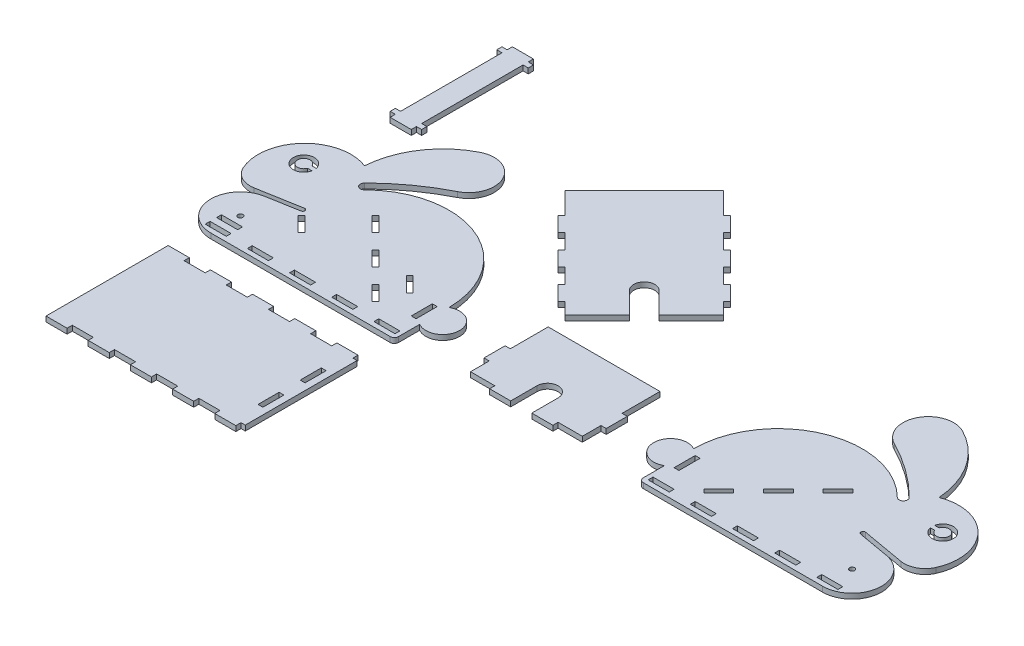
SolidWorks part; units mm, degrees
ref_plane "Front Plane" through (0, 0, 0) normal (0, 0, 1) x (1, 0, 0)
ref_plane "Top Plane" through (0, 0, 0) normal (0, 1, 0) x (1, 0, 0)
ref_plane "Right Plane" through (0, 0, 0) normal (1, 0, 0) x (0, 0, -1)
sketch "Sketch1" plane through (0, 0, 0) normal (0, 1, 0) x (1, 0, 0)
  line L0 (57.15, -63.5) -> (57.15, 63.5) construction
  line L1 (-76.2, 63.5) -> (76.2, 63.5) construction
  line L2 (-76.2, 63.5) -> (-76.2, -63.5) construction
  line L3 (-76.2, -63.5) -> (76.2, -63.5) construction
  line L4 (76.2, 63.5) -> (76.2, -63.5) construction
  line L5 (-76.2, 63.5) -> (76.2, -63.5) construction
  line L6 (-76.2, -63.5) -> (76.2, 63.5) construction
  point P0 (0, 0)
  dimension "D1" = 152.4
  dimension "D2" = 127
  dimension "D3" = 19.05
sketch "Sketch3" plane through (0, 0, 0) normal (0, 1, 0) x (1, 0, 0)
  line L0 (-76.2, -63.5) -> (76.2, -63.5) construction
  line L1 (-76.2, 63.5) -> (-76.2, -63.5) construction
  circle A0 centre (-50.8, -38.1) radius 25.4 construction
  dimension "D1" = 50.8
sketch "Sketch5" plane through (0, 0, 0) normal (0, 1, 0) x (1, 0, 0)
  line L1 (6.35, -55.88) -> (57.15, -55.88) construction
  line L2 (31.75, -55.88) -> (31.75, -63.5) construction
  line L3 (-76.2, -63.5) -> (76.2, -63.5) construction
  line L4 (57.15, -63.5) -> (57.15, 63.5) construction
  arc A0 (6.35, -55.88) -> (57.15, -55.88) centre (31.75, -17.3567) ccw construction
  dimension "D1" = 7.62
  dimension "D2" = 50.8
sketch "Sketch6" plane through (0, 0, 0) normal (0, 1, 0) x (1, 0, 0)
  line L0 (-50.8, -38.1) -> (-50.8, -55.88) construction
  line L1 (-50.8, -55.88) -> (57.15, -55.88) construction
  line L2 (-53.8875, -20.5901) -> (-35.1269, -17.2821) construction
  line L3 (-35.5679, -14.7807) -> (-35.1269, -17.2821) construction
  line L4 (-53.8875, -20.5901) -> (-35.1269, -20.5901) construction
  line L5 (-35.1269, -20.5901) -> (-35.1269, -17.2821) construction
  line L6 (-35.5679, -14.7807) -> (-61.3497, -19.3267) construction
  line L7 (59.69, -53.34) -> (57.15, -53.34) construction
  line L8 (57.15, -53.34) -> (57.15, -55.88) construction
  line L9 (59.69, -53.34) -> (59.69, -40.64) construction
  line L10 (59.69, -40.64) -> (64.77, -31.8412) construction
  line L11 (64.77, -31.8412) -> (59.69, -23.0424) construction
  line L12 (59.69, -23.0424) -> (59.69, -40.64) construction
  line L13 (-27.031, 12.8787) -> (8.89, -23.0424) construction
  line L14 (8.89, -23.0424) -> (59.69, -23.0424) construction
  line L15 (-27.031, 12.8787) -> (-28.8271, 14.6747) construction
  line L16 (-28.8271, 14.6747) -> (-30.6231, 16.4708) construction
  line L17 (-30.6231, 16.4708) -> (-39.6034, 25.451) construction
  line L18 (-11.8373, 67.2263) -> (-4.9647, 53.6239) construction
  line L19 (-4.9647, 53.6239) -> (1.9078, 40.0215) construction
  line L20 (-75.1597, -11.9793) -> (-49.6295, -0.6281) construction
  line L21 (-49.6295, -0.6281) -> (-39.6034, 25.451) construction
  line L22 (-59.0189, 8.2912) -> (-75.1597, -11.9793) construction
  line L23 (-59.0189, 8.2912) -> (-39.6034, 25.451) construction
  line L26 (-55.4268, 9.5612) -> (-52.7972, 9.5612) construction
  line L27 (-55.4268, 7.0212) -> (-52.7972, 7.0212) construction
  line L28 (-52.7972, 9.5612) -> (-52.7972, 7.0212) construction
  line L29 (-55.4268, 9.5612) -> (-55.4268, 7.0212) construction
  arc A0 (-50.8, -55.88) -> (-53.8875, -20.5901) centre (-50.8, -38.1) cw construction
  arc A1 (-35.1269, -17.2821) -> (-35.5679, -14.7807) centre (-35.3474, -16.0314) ccw construction
  arc A2 (57.15, -55.88) -> (59.69, -53.34) centre (57.15, -53.34) ccw construction
  arc A3 (59.69, -40.64) -> (59.69, -23.0424) centre (64.77, -31.8412) ccw construction
  arc A4 (59.69, -23.0424) -> (-27.031, 12.8787) centre (8.89, -23.0424) ccw construction
  arc A5 (-27.031, 12.8787) -> (-30.6231, 16.4708) centre (-28.8271, 14.6747) cw construction
  arc A6 (-30.6231, 16.4708) -> (1.9078, 40.0215) centre (59.1794, -73.3318) cw construction
  arc A7 (1.9078, 40.0215) -> (-11.8373, 67.2263) centre (-4.9647, 53.6239) ccw construction
  arc A8 (-11.8373, 67.2263) -> (-39.6034, 25.451) centre (11.0713, 21.885) ccw construction
  arc A9 (-61.3497, -19.3267) -> (-75.1597, -11.9793) centre (-63.5551, -6.8197) cw construction
  arc A10 (-75.1597, -11.9793) -> (-39.6034, 25.451) centre (-49.6295, -0.6281) cw construction
  arc A11 (-55.4268, 9.5612) -> (-55.4268, 7.0212) centre (-59.0189, 8.2912) ccw construction
  arc A13 (-52.7972, 9.5612) -> (-52.7972, 7.0212) centre (-59.0189, 8.2912) ccw construction
  dimension "D2" = 1.27
  dimension "D3" = 2.54
  dimension "D5" = 10.16
  dimension "D8" = 2.54
  dimension "D11" = 15.24
  dimension "D12" = 127
  dimension "D13" = 50.8
  dimension "D15" = 12.7
  dimension "D16" = 27.94
  dimension "D18" = 7.62
  dimension "D19" = 2.54
  dimension "D1" = 10
  dimension "D4" = 30
  dimension "D6" = 12.7
  dimension "D7" = 135
  dimension "D9" = 180
  dimension "D10" = 50.8
  dimension "D14" = 12.7
  dimension "D17" = 135
  dimension "D20" = 170
  dimension "D21" = 2.54
  dimension "D22" = 19.05
sketch "Sketch7" plane through (0, 0, 0) normal (0, 1, 0) x (1, 0, 0)
  line L0 (-50.8, -55.88) -> (57.15, -55.88) construction
  line L1 (59.69, -53.34) -> (59.69, -40.64) construction
  line L2 (-35.5679, -14.7807) -> (-61.3497, -19.3267) construction
  line L3 (-53.8875, -20.5901) -> (-35.1269, -17.2821) construction
  line L4 (25.4, -51.4985) -> (0, -51.4985) construction
  line L5 (19.05, -50.038) -> (31.75, -50.038)
  line L6 (-50.8, -55.88) -> (57.15, -55.88)
  line L7 (59.69, -53.34) -> (59.69, -40.64)
  line L8 (-35.5679, -14.7807) -> (-61.3497, -19.3267)
  line L9 (-53.8875, -20.5901) -> (-35.1269, -17.2821)
  line L10 (-55.4268, 9.5612) -> (-52.7972, 9.5612) construction
  line L11 (-55.4268, 7.0212) -> (-52.7972, 7.0212) construction
  line L12 (-55.4268, 9.5612) -> (-52.7972, 9.5612)
  line L13 (-55.4268, 7.0212) -> (-52.7972, 7.0212)
  line L14 (50.8, -51.4985) -> (25.4, -51.4985) construction
  line L15 (44.45, -50.038) -> (57.15, -50.038)
  line L16 (44.45, -50.038) -> (44.45, -52.959)
  line L17 (44.45, -52.959) -> (57.15, -52.959)
  line L18 (57.15, -50.038) -> (57.15, -52.959)
  line L19 (44.45, -50.038) -> (57.15, -52.959) construction
  line L20 (44.45, -52.959) -> (57.15, -50.038) construction
  line L21 (19.05, -50.038) -> (19.05, -52.959)
  line L22 (19.05, -52.959) -> (31.75, -52.959)
  line L23 (31.75, -50.038) -> (31.75, -52.959)
  line L24 (19.05, -50.038) -> (31.75, -52.959) construction
  line L25 (19.05, -52.959) -> (31.75, -50.038) construction
  line L26 (0, -51.4985) -> (-25.4, -51.4985) construction
  line L27 (-6.35, -50.038) -> (6.35, -50.038)
  line L28 (-6.35, -50.038) -> (-6.35, -52.959)
  line L29 (-6.35, -52.959) -> (6.35, -52.959)
  line L30 (6.35, -50.038) -> (6.35, -52.959)
  line L31 (-6.35, -50.038) -> (6.35, -52.959) construction
  line L32 (-6.35, -52.959) -> (6.35, -50.038) construction
  line L33 (-25.4, -51.4985) -> (-50.8, -51.4985) construction
  line L34 (-31.75, -50.038) -> (-19.05, -50.038)
  line L35 (-31.75, -50.038) -> (-31.75, -52.959)
  line L36 (-31.75, -52.959) -> (-19.05, -52.959)
  line L37 (-19.05, -50.038) -> (-19.05, -52.959)
  line L38 (-31.75, -50.038) -> (-19.05, -52.959) construction
  line L39 (-31.75, -52.959) -> (-19.05, -50.038) construction
  line L40 (57.15, -51.4985) -> (54.229, -51.4985) construction
  line L41 (-57.15, -50.038) -> (-44.45, -50.038)
  line L42 (-57.15, -50.038) -> (-57.15, -52.959)
  line L43 (-57.15, -52.959) -> (-44.45, -52.959)
  line L44 (-44.45, -50.038) -> (-44.45, -52.959)
  line L45 (-57.15, -50.038) -> (-44.45, -52.959) construction
  line L46 (-57.15, -52.959) -> (-44.45, -50.038) construction
  line L47 (54.229, -51.4985) -> (54.229, -32.4485) construction
  line L49 (52.7685, -26.0985) -> (55.6895, -26.0985)
  line L50 (52.7685, -26.0985) -> (52.7685, -38.7985)
  line L51 (52.7685, -38.7985) -> (55.6895, -38.7985)
  line L52 (55.6895, -26.0985) -> (55.6895, -38.7985)
  line L53 (52.7685, -26.0985) -> (55.6895, -38.7985) construction
  line L54 (52.7685, -38.7985) -> (55.6895, -26.0985) construction
  arc A0 (-53.8875, -20.5901) -> (-50.8, -55.88) centre (-50.8, -38.1) ccw construction
  arc A1 (57.15, -55.88) -> (59.69, -53.34) centre (57.15, -53.34) ccw construction
  arc A2 (59.69, -40.64) -> (59.69, -23.0424) centre (64.77, -31.8412) ccw construction
  arc A3 (59.69, -23.0424) -> (-27.031, 12.8787) centre (8.89, -23.0424) ccw construction
  arc A4 (-30.6231, 16.4708) -> (-27.031, 12.8787) centre (-28.8271, 14.6747) ccw construction
  arc A5 (1.9078, 40.0215) -> (-30.6231, 16.4708) centre (59.1794, -73.3318) ccw construction
  arc A6 (1.9078, 40.0215) -> (-11.8373, 67.2263) centre (-4.9647, 53.6239) ccw construction
  arc A7 (-11.8373, 67.2263) -> (-39.6034, 25.451) centre (11.0713, 21.885) ccw construction
  arc A8 (-39.6034, 25.451) -> (-75.1597, -11.9793) centre (-49.6295, -0.6281) ccw construction
  arc A9 (-75.1597, -11.9793) -> (-61.3497, -19.3267) centre (-63.5551, -6.8197) ccw construction
  arc A10 (-35.1269, -17.2821) -> (-35.5679, -14.7807) centre (-35.3474, -16.0314) ccw construction
  arc A13 (-53.8875, -20.5901) -> (-50.8, -55.88) centre (-50.8, -38.1) ccw
  arc A14 (57.15, -55.88) -> (59.69, -53.34) centre (57.15, -53.34) ccw
  arc A15 (59.69, -40.64) -> (59.69, -23.0424) centre (64.77, -31.8412) ccw
  arc A16 (59.69, -23.0424) -> (-27.031, 12.8787) centre (8.89, -23.0424) ccw
  arc A17 (-30.6231, 16.4708) -> (-27.031, 12.8787) centre (-28.8271, 14.6747) ccw
  arc A18 (1.9078, 40.0215) -> (-30.6231, 16.4708) centre (59.1794, -73.3318) ccw
  arc A19 (1.9078, 40.0215) -> (-11.8373, 67.2263) centre (-4.9647, 53.6239) ccw
  arc A20 (-11.8373, 67.2263) -> (-39.6034, 25.451) centre (11.0713, 21.885) ccw
  arc A21 (-39.6034, 25.451) -> (-75.1597, -11.9793) centre (-49.6295, -0.6281) ccw
  arc A22 (-75.1597, -11.9793) -> (-61.3497, -19.3267) centre (-63.5551, -6.8197) ccw
  arc A23 (-35.1269, -17.2821) -> (-35.5679, -14.7807) centre (-35.3474, -16.0314) ccw
  arc A24 (-55.4268, 9.5612) -> (-55.4268, 7.0212) centre (-59.0189, 8.2912) ccw construction
  arc A25 (-52.7972, 9.5612) -> (-52.7972, 7.0212) centre (-59.0189, 8.2912) ccw construction
  arc A26 (-55.4268, 9.5612) -> (-55.4268, 7.0212) centre (-59.0189, 8.2912) ccw
  arc A27 (-52.7972, 9.5612) -> (-52.7972, 7.0212) centre (-59.0189, 8.2912) ccw
  point P29 (50.8, -51.4985)
  dimension "D1" = 2.921
  dimension "D2" = 12.7
  dimension "D3" = 2.921
  dimension "D4" = 2.54
  dimension "D5" = 25.4
  dimension "D6" = 19.05
sketch "Sketch9" plane through (0, 0, 0) normal (0, 1, 0) x (1, 0, 0)
  line L0 (-39.0097, 50.0021) -> (52.7685, -41.7762) construction
  line L1 (-39.0097, 50.0021) -> (-47.2716, 41.7402) construction
  line L2 (52.7685, -41.7762) -> (44.5067, -50.038) construction
  line L3 (-47.2716, 41.7402) -> (44.5067, -50.038) construction
  line L4 (-39.0097, 50.0021) -> (44.5067, -50.038) construction
  line L5 (52.7685, -41.7762) -> (-47.2716, 41.7402) construction
  line L6 (2.7485, -0.018) -> (2.7485, -55.88) construction
  line L7 (-50.8, -55.88) -> (57.15, -55.88) construction
  line L8 (44.5067, -50.038) -> (7.2565, -50.038) construction
  line L9 (19.05, -50.038) -> (31.75, -50.038) construction
  line L11 (52.7685, -26.0985) -> (52.7685, -38.7985) construction
  point P1 (2.7485, -0.018)
  dimension "D1" = 129.794
  dimension "D2" = 11.684
  dimension "D3" = 45
sketch "Sketch10" plane through (0, 0, 0) normal (0, 1, 0) x (1, 0, 0)
  line L0 (24.4807, -34.1429) -> (33.4609, -43.1232)
  line L1 (24.4807, -34.1429) -> (26.5462, -32.0775)
  line L2 (33.4609, -43.1232) -> (35.5264, -41.0577)
  line L3 (26.5462, -32.0775) -> (35.5264, -41.0577)
  line L4 (24.4807, -34.1429) -> (35.5264, -41.0577) construction
  line L5 (33.4609, -43.1232) -> (26.5462, -32.0775) construction
  line L6 (44.45, -50.038) -> (57.15, -50.038) construction
  line L7 (57.15, -50.038) -> (57.15, -52.959) construction
  line L8 (-47.2716, 41.7402) -> (44.5067, -50.038) construction
  line L9 (30.0036, -37.6003) -> (12.043, -19.6398) construction
  line L10 (25.4, -51.4985) -> (0, -51.4985) construction
  line L11 (8.5856, -14.117) -> (17.5659, -23.0972)
  line L12 (8.5856, -14.117) -> (6.5202, -16.1824)
  line L13 (17.5659, -23.0972) -> (15.5004, -25.1627)
  line L14 (6.5202, -16.1824) -> (15.5004, -25.1627)
  line L15 (8.5856, -14.117) -> (15.5004, -25.1627) construction
  line L16 (17.5659, -23.0972) -> (6.5202, -16.1824) construction
  line L18 (12.043, -19.6398) -> (-5.9175, -1.6793) construction
  line L19 (-9.3749, 3.8435) -> (-0.3946, -5.1367)
  line L20 (-9.3749, 3.8435) -> (-11.4403, 1.7781)
  line L21 (-0.3946, -5.1367) -> (-2.4601, -7.2022)
  line L22 (-11.4403, 1.7781) -> (-2.4601, -7.2022)
  line L23 (-9.3749, 3.8435) -> (-2.4601, -7.2022) construction
  line L24 (-0.3946, -5.1367) -> (-11.4403, 1.7781) construction
  point P1 (30.0036, -37.6003)
  dimension "D1" = 12.7
sketch "Sketch11" plane through (0, 0, 0) normal (0, 1, 0) x (1, 0, 0)
  line L0 (-31.75, -50.038) -> (-19.05, -50.038) construction
  line L1 (-35.8243, -24.638) -> (14.9757, -24.638) construction
  line L2 (-35.8243, -24.638) -> (-35.8243, -50.038) construction
  line L3 (-35.8243, -50.038) -> (14.9757, -50.038) construction
  line L4 (14.9757, -24.638) -> (14.9757, -50.038) construction
  line L5 (-35.8243, -24.638) -> (14.9757, -50.038) construction
  line L6 (-35.8243, -50.038) -> (14.9757, -24.638) construction
  line L7 (6.5202, -16.1824) -> (15.5004, -25.1627) construction
  point P0 (-10.4243, -37.338)
  dimension "D1" = 25.4
  dimension "D2" = 50.8
sketch "Sketch12" plane through (0, 0, 0) normal (0, 1, 0) x (1, 0, 0)
  line L0 (59.69, -53.34) -> (59.69, -40.64) construction
  line L1 (55.6895, -26.0985) -> (55.6895, -38.7985) construction
  line L2 (52.7685, -26.0985) -> (55.6895, -26.0985) construction
  line L3 (52.7685, -26.0985) -> (52.7685, -38.7985) construction
  line L4 (52.7685, -38.7985) -> (55.6895, -38.7985) construction
  line L5 (-50.8, -55.88) -> (57.15, -55.88) construction
  line L6 (44.45, -52.959) -> (57.15, -52.959) construction
  line L7 (57.15, -50.038) -> (57.15, -52.959) construction
  line L8 (44.45, -50.038) -> (57.15, -50.038) construction
  line L9 (44.45, -50.038) -> (44.45, -52.959) construction
  line L10 (19.05, -50.038) -> (31.75, -50.038) construction
  line L11 (19.05, -52.959) -> (31.75, -52.959) construction
  line L12 (31.75, -50.038) -> (31.75, -52.959) construction
  line L13 (19.05, -50.038) -> (19.05, -52.959) construction
  line L14 (6.35, -50.038) -> (6.35, -52.959) construction
  line L15 (-6.35, -50.038) -> (6.35, -50.038) construction
  line L16 (-6.35, -52.959) -> (6.35, -52.959) construction
  line L17 (-6.35, -50.038) -> (-6.35, -52.959) construction
  line L18 (-19.05, -50.038) -> (-19.05, -52.959) construction
  line L19 (-31.75, -50.038) -> (-19.05, -50.038) construction
  line L20 (-31.75, -52.959) -> (-19.05, -52.959) construction
  line L21 (-31.75, -50.038) -> (-31.75, -52.959) construction
  line L22 (-57.15, -50.038) -> (-44.45, -50.038) construction
  line L23 (-44.45, -50.038) -> (-44.45, -52.959) construction
  line L24 (-57.15, -52.959) -> (-44.45, -52.959) construction
  line L25 (-57.15, -50.038) -> (-57.15, -52.959) construction
  line L26 (-53.8875, -20.5901) -> (-35.1269, -17.2821) construction
  line L27 (-35.5679, -14.7807) -> (-61.3497, -19.3267) construction
  line L28 (-9.3749, 3.8435) -> (-11.4403, 1.7781) construction
  line L29 (-11.4403, 1.7781) -> (-2.4601, -7.2022) construction
  line L30 (-0.3946, -5.1367) -> (-2.4601, -7.2022) construction
  line L31 (-9.3749, 3.8435) -> (-0.3946, -5.1367) construction
  line L32 (6.5202, -16.1824) -> (15.5004, -25.1627) construction
  line L33 (8.5856, -14.117) -> (6.5202, -16.1824) construction
  line L34 (17.5659, -23.0972) -> (15.5004, -25.1627) construction
  line L35 (59.69, -53.34) -> (59.69, -40.64)
  line L36 (55.6895, -26.0985) -> (55.6895, -38.7985)
  line L37 (52.7685, -26.0985) -> (55.6895, -26.0985)
  line L38 (52.7685, -26.0985) -> (52.7685, -38.7985)
  line L39 (52.7685, -38.7985) -> (55.6895, -38.7985)
  line L40 (-50.8, -55.88) -> (57.15, -55.88)
  line L41 (44.45, -52.959) -> (57.15, -52.959)
  line L42 (57.15, -50.038) -> (57.15, -52.959)
  line L43 (44.45, -50.038) -> (57.15, -50.038)
  line L44 (44.45, -50.038) -> (44.45, -52.959)
  line L45 (19.05, -50.038) -> (31.75, -50.038)
  line L46 (19.05, -52.959) -> (31.75, -52.959)
  line L47 (31.75, -50.038) -> (31.75, -52.959)
  line L48 (19.05, -50.038) -> (19.05, -52.959)
  line L49 (6.35, -50.038) -> (6.35, -52.959)
  line L50 (-6.35, -50.038) -> (6.35, -50.038)
  line L51 (-6.35, -52.959) -> (6.35, -52.959)
  line L52 (-6.35, -50.038) -> (-6.35, -52.959)
  line L53 (-19.05, -50.038) -> (-19.05, -52.959)
  line L54 (-31.75, -50.038) -> (-19.05, -50.038)
  line L55 (-31.75, -52.959) -> (-19.05, -52.959)
  line L56 (-31.75, -50.038) -> (-31.75, -52.959)
  line L57 (-57.15, -50.038) -> (-44.45, -50.038)
  line L58 (-44.45, -50.038) -> (-44.45, -52.959)
  line L59 (-57.15, -52.959) -> (-44.45, -52.959)
  line L60 (-57.15, -50.038) -> (-57.15, -52.959)
  line L61 (-53.8875, -20.5901) -> (-35.1269, -17.2821)
  line L62 (-35.5679, -14.7807) -> (-61.3497, -19.3267)
  line L63 (-9.3749, 3.8435) -> (-11.4403, 1.7781)
  line L64 (-11.4403, 1.7781) -> (-2.4601, -7.2022)
  line L65 (-0.3946, -5.1367) -> (-2.4601, -7.2022)
  line L66 (-9.3749, 3.8435) -> (-0.3946, -5.1367)
  line L67 (6.5202, -16.1824) -> (15.5004, -25.1627)
  line L68 (8.5856, -14.117) -> (6.5202, -16.1824)
  line L69 (17.5659, -23.0972) -> (15.5004, -25.1627)
  line L70 (8.5856, -14.117) -> (17.5659, -23.0972) construction
  line L71 (26.5462, -32.0775) -> (35.5264, -41.0577) construction
  line L72 (24.4807, -34.1429) -> (26.5462, -32.0775) construction
  line L73 (24.4807, -34.1429) -> (33.4609, -43.1232) construction
  line L74 (33.4609, -43.1232) -> (35.5264, -41.0577) construction
  line L75 (8.5856, -14.117) -> (17.5659, -23.0972)
  line L76 (26.5462, -32.0775) -> (35.5264, -41.0577)
  line L77 (24.4807, -34.1429) -> (26.5462, -32.0775)
  line L78 (24.4807, -34.1429) -> (33.4609, -43.1232)
  line L79 (33.4609, -43.1232) -> (35.5264, -41.0577)
  line L80 (-55.4268, 9.5612) -> (-52.7972, 9.5612) construction
  line L81 (-55.4268, 7.0212) -> (-52.7972, 7.0212) construction
  line L82 (-55.4268, 9.5612) -> (-52.7972, 9.5612)
  line L83 (-55.4268, 7.0212) -> (-52.7972, 7.0212)
  line L84 (57.15, -51.4985) -> (133.35, -51.4985) construction
  line L85 (133.35, -51.4985) -> (133.35, -26.0985) construction
  line L86 (322.1268, 7.0212) -> (319.4972, 7.0212)
  line L87 (322.1268, 9.5612) -> (319.4972, 9.5612)
  line L88 (233.2391, -43.1232) -> (231.1736, -41.0577)
  line L89 (242.2193, -34.1429) -> (233.2391, -43.1232)
  line L90 (242.2193, -34.1429) -> (240.1538, -32.0775)
  line L91 (240.1538, -32.0775) -> (231.1736, -41.0577)
  line L92 (258.1144, -14.117) -> (249.1341, -23.0972)
  line L93 (249.1341, -23.0972) -> (251.1996, -25.1627)
  line L94 (258.1144, -14.117) -> (260.1798, -16.1824)
  line L95 (260.1798, -16.1824) -> (251.1996, -25.1627)
  line L96 (276.0749, 3.8435) -> (267.0946, -5.1367)
  line L97 (267.0946, -5.1367) -> (269.1601, -7.2022)
  line L98 (278.1403, 1.7781) -> (269.1601, -7.2022)
  line L99 (276.0749, 3.8435) -> (278.1403, 1.7781)
  line L100 (302.2679, -14.7807) -> (328.0497, -19.3267)
  line L101 (320.5875, -20.5901) -> (301.8269, -17.2821)
  line L102 (323.85, -50.038) -> (323.85, -52.959)
  line L103 (323.85, -52.959) -> (311.15, -52.959)
  line L104 (311.15, -50.038) -> (311.15, -52.959)
  line L105 (323.85, -50.038) -> (311.15, -50.038)
  line L106 (298.45, -50.038) -> (298.45, -52.959)
  line L107 (298.45, -52.959) -> (285.75, -52.959)
  line L108 (298.45, -50.038) -> (285.75, -50.038)
  line L109 (285.75, -50.038) -> (285.75, -52.959)
  line L110 (273.05, -50.038) -> (273.05, -52.959)
  line L111 (273.05, -52.959) -> (260.35, -52.959)
  line L112 (273.05, -50.038) -> (260.35, -50.038)
  line L113 (260.35, -50.038) -> (260.35, -52.959)
  line L114 (247.65, -50.038) -> (247.65, -52.959)
  line L115 (234.95, -50.038) -> (234.95, -52.959)
  line L116 (247.65, -52.959) -> (234.95, -52.959)
  line L117 (247.65, -50.038) -> (234.95, -50.038)
  line L118 (222.25, -50.038) -> (222.25, -52.959)
  line L119 (222.25, -50.038) -> (209.55, -50.038)
  line L120 (209.55, -50.038) -> (209.55, -52.959)
  line L121 (222.25, -52.959) -> (209.55, -52.959)
  line L122 (317.5, -55.88) -> (209.55, -55.88)
  line L123 (213.9315, -38.7985) -> (211.0105, -38.7985)
  line L124 (213.9315, -26.0985) -> (213.9315, -38.7985)
  line L125 (213.9315, -26.0985) -> (211.0105, -26.0985)
  line L126 (211.0105, -26.0985) -> (211.0105, -38.7985)
  line L127 (207.01, -53.34) -> (207.01, -40.64)
  line L128 (-50.8, -38.1) -> (-50.8, -44.6405) construction
  line L129 (-57.15, -43.18) -> (-44.45, -43.18)
  line L130 (-57.15, -43.18) -> (-57.15, -46.101)
  line L131 (-57.15, -46.101) -> (-44.45, -46.101)
  line L132 (-44.45, -43.18) -> (-44.45, -46.101)
  line L133 (-57.15, -43.18) -> (-44.45, -46.101) construction
  line L134 (-57.15, -46.101) -> (-44.45, -43.18) construction
  line L135 (-44.9915, -5.0819) -> (-9.0705, -41.0029) construction
  line L136 (-56.9702, 67.9626) -> (34.808, -23.8157) construction
  line L137 (-44.9915, -5.0819) -> (-24.786, 15.1237) construction
  line L138 (-39.0097, 50.0021) -> (52.7685, -41.7762) construction
  line L139 (-65.2321, 59.7007) -> (26.5462, -32.0775) construction
  line L140 (-47.2716, 41.7402) -> (44.5067, -50.038) construction
  line L141 (26.5462, -32.0775) -> (34.808, -23.8157) construction
  line L142 (-65.2321, 59.7007) -> (-56.9702, 67.9626) construction
  line L143 (30.3179, -19.3255) -> (39.2981, -28.3058)
  line L144 (30.3179, -19.3255) -> (32.3833, -17.2601)
  line L145 (39.2981, -28.3058) -> (41.3636, -26.2403)
  line L146 (32.3833, -17.2601) -> (41.3636, -26.2403)
  line L147 (30.3179, -19.3255) -> (41.3636, -26.2403) construction
  line L148 (39.2981, -28.3058) -> (32.3833, -17.2601) construction
  line L149 (-9.0705, -41.0029) -> (11.1351, -20.7973) construction
  line L150 (-24.786, 15.1237) -> (11.1351, -20.7973) construction
  line L151 (-44.9915, -5.0819) -> (11.1351, -20.7973) construction
  line L152 (-9.0705, -41.0029) -> (-24.786, 15.1237) construction
  line L153 (-33.7114, -20.493) -> (-24.7311, -29.4732)
  line L154 (-33.7114, -20.493) -> (-31.6459, -18.4275)
  line L155 (-24.7311, -29.4732) -> (-22.6657, -27.4078)
  line L156 (-31.6459, -18.4275) -> (-22.6657, -27.4078)
  line L157 (-33.7114, -20.493) -> (-22.6657, -27.4078) construction
  line L158 (-24.7311, -29.4732) -> (-31.6459, -18.4275) construction
  line L159 (-33.7114, -20.493) -> (-35.7768, -18.4275) construction
  line L160 (-35.7768, -18.4275) -> (-33.7114, -16.362) construction
  line L161 (-33.7114, -16.362) -> (-31.6459, -18.4275) construction
  line L162 (-31.6459, -18.4275) -> (-33.7114, -16.362) construction
  arc A0 (-39.6034, 25.451) -> (-75.1597, -11.9793) centre (-49.6295, -0.6281) ccw construction
  arc A1 (-11.8373, 67.2263) -> (-39.6034, 25.451) centre (11.0713, 21.885) ccw construction
  arc A2 (1.9078, 40.0215) -> (-11.8373, 67.2263) centre (-4.9647, 53.6239) ccw construction
  arc A3 (1.9078, 40.0215) -> (-30.6231, 16.4708) centre (59.1794, -73.3318) ccw construction
  arc A4 (-30.6231, 16.4708) -> (-27.031, 12.8787) centre (-28.8271, 14.6747) ccw construction
  arc A5 (59.69, -23.0424) -> (-27.031, 12.8787) centre (8.89, -23.0424) ccw construction
  arc A6 (59.69, -40.64) -> (59.69, -23.0424) centre (64.77, -31.8412) ccw construction
  arc A7 (57.15, -55.88) -> (59.69, -53.34) centre (57.15, -53.34) ccw construction
  arc A8 (-53.8875, -20.5901) -> (-50.8, -55.88) centre (-50.8, -38.1) ccw construction
  arc A9 (-35.1269, -17.2821) -> (-35.5679, -14.7807) centre (-35.3474, -16.0314) ccw construction
  arc A10 (-75.1597, -11.9793) -> (-61.3497, -19.3267) centre (-63.5551, -6.8197) ccw construction
  arc A11 (-39.6034, 25.451) -> (-75.1597, -11.9793) centre (-49.6295, -0.6281) ccw
  arc A12 (-11.8373, 67.2263) -> (-39.6034, 25.451) centre (11.0713, 21.885) ccw
  arc A13 (1.9078, 40.0215) -> (-11.8373, 67.2263) centre (-4.9647, 53.6239) ccw
  arc A14 (1.9078, 40.0215) -> (-30.6231, 16.4708) centre (59.1794, -73.3318) ccw
  arc A15 (-30.6231, 16.4708) -> (-27.031, 12.8787) centre (-28.8271, 14.6747) ccw
  arc A16 (59.69, -23.0424) -> (-27.031, 12.8787) centre (8.89, -23.0424) ccw
  arc A17 (59.69, -40.64) -> (59.69, -23.0424) centre (64.77, -31.8412) ccw
  arc A18 (57.15, -55.88) -> (59.69, -53.34) centre (57.15, -53.34) ccw
  arc A19 (-53.8875, -20.5901) -> (-50.8, -55.88) centre (-50.8, -38.1) ccw
  arc A20 (-35.1269, -17.2821) -> (-35.5679, -14.7807) centre (-35.3474, -16.0314) ccw
  arc A21 (-75.1597, -11.9793) -> (-61.3497, -19.3267) centre (-63.5551, -6.8197) ccw
  arc A22 (-52.7972, 9.5612) -> (-52.7972, 7.0212) centre (-59.0189, 8.2912) ccw construction
  arc A23 (-55.4268, 9.5612) -> (-55.4268, 7.0212) centre (-59.0189, 8.2912) ccw construction
  arc A24 (-52.7972, 9.5612) -> (-52.7972, 7.0212) centre (-59.0189, 8.2912) ccw
  arc A25 (-55.4268, 9.5612) -> (-55.4268, 7.0212) centre (-59.0189, 8.2912) ccw
  circle A26 centre (-50.8, -38.1) radius 1.524
  circle A27 centre (317.5, -38.1) radius 1.524
  arc A28 (322.1268, 9.5612) -> (322.1268, 7.0212) centre (325.7189, 8.2912) cw
  arc A29 (319.4972, 9.5612) -> (319.4972, 7.0212) centre (325.7189, 8.2912) cw
  arc A30 (341.8597, -11.9793) -> (328.0497, -19.3267) centre (330.2551, -6.8197) cw
  arc A31 (301.8269, -17.2821) -> (302.2679, -14.7807) centre (302.0474, -16.0314) cw
  arc A32 (320.5875, -20.5901) -> (317.5, -55.88) centre (317.5, -38.1) cw
  arc A33 (209.55, -55.88) -> (207.01, -53.34) centre (209.55, -53.34) cw
  arc A34 (207.01, -40.64) -> (207.01, -23.0424) centre (201.93, -31.8412) cw
  arc A35 (207.01, -23.0424) -> (293.731, 12.8787) centre (257.81, -23.0424) cw
  arc A36 (297.3231, 16.4708) -> (293.731, 12.8787) centre (295.5271, 14.6747) cw
  arc A37 (264.7922, 40.0215) -> (297.3231, 16.4708) centre (207.5206, -73.3318) cw
  arc A38 (264.7922, 40.0215) -> (278.5373, 67.2263) centre (271.6647, 53.6239) cw
  arc A39 (278.5373, 67.2263) -> (306.3034, 25.451) centre (255.6287, 21.885) cw
  arc A40 (306.3034, 25.451) -> (341.8597, -11.9793) centre (316.3295, -0.6281) cw
  point P58 (26.5462, -32.0775)
  point P142 (-50.8, -44.6405)
  point P157 (35.8407, -22.7829)
  point P158 (-16.9282, -12.9396)
  point P159 (-28.1885, -23.9504)
  dimension "D1" = 3.048
  dimension "D2" = 76.2
  dimension "D3" = 25.4
  dimension "D4" = 5.08
  dimension "D5" = 19.05
  dimension "D6" = 6.35
  dimension "D7" = 28.575
  dimension "D8" = 50.8
  dimension "D9" = 2.921
ref_plane "Plane1" through (101.6, 0, 0) normal (1, 0, 0) x (0, 0, -1)
sketch "Sketch13" plane through (0, 0, 0) normal (0, 1, 0) x (1, 0, 0)
  line L0 (-57.15, -52.959) -> (-57.15, -78.359) construction
  line L1 (59.69, -53.34) -> (59.69, -78.359) construction
  line L2 (-57.15, -78.359) -> (-31.75, -78.359) construction
  line L3 (-31.75, -78.359) -> (-6.35, -78.359) construction
  line L4 (-6.35, -78.359) -> (19.05, -78.359) construction
  line L5 (19.05, -78.359) -> (44.45, -78.359) construction
  line L6 (50.8, -51.4985) -> (25.4, -51.4985) construction
  line L7 (-57.15, -78.359) -> (-57.15, -75.2348)
  line L8 (52.7685, -92.964) -> (55.6895, -92.964)
  line L9 (-57.15, -75.2348) -> (-44.45, -75.2348)
  line L10 (-44.45, -75.2348) -> (-44.45, -78.359)
  line L11 (-44.45, -78.359) -> (-31.75, -78.359)
  line L12 (-31.75, -78.359) -> (-31.75, -75.2348)
  line L13 (52.7685, -92.964) -> (52.7685, -105.664)
  line L14 (-31.75, -75.2348) -> (-19.05, -75.2348)
  line L15 (-19.05, -75.2348) -> (-19.05, -78.359)
  line L16 (-19.05, -78.359) -> (-6.35, -78.359)
  line L17 (-6.35, -78.359) -> (-6.35, -75.2348)
  line L18 (-6.35, -75.2348) -> (6.35, -75.2348)
  line L19 (6.35, -75.2348) -> (6.35, -78.359)
  line L20 (6.35, -78.359) -> (19.05, -78.359)
  line L21 (19.05, -78.359) -> (19.05, -75.2348)
  line L22 (19.05, -75.2348) -> (31.75, -75.2348)
  line L23 (31.75, -75.2348) -> (31.75, -78.359)
  line L24 (31.75, -78.359) -> (44.45, -78.359)
  line L25 (44.45, -78.359) -> (44.45, -75.2348)
  line L26 (44.45, -75.2348) -> (57.15, -75.2348)
  line L27 (57.15, -75.2348) -> (57.15, -78.359)
  line L29 (44.45, -50.038) -> (57.15, -50.038) construction
  line L30 (-57.15, -78.359) -> (-57.15, -145.669)
  line L31 (-57.15, -112.014) -> (57.15, -112.014) construction
  line L32 (57.15, -145.669) -> (57.15, -78.359) construction
  line L33 (19.05, -145.669) -> (44.45, -145.669) construction
  line L34 (-6.35, -145.669) -> (19.05, -145.669) construction
  line L35 (-31.75, -145.669) -> (-6.35, -145.669) construction
  line L36 (-57.15, -145.669) -> (-31.75, -145.669) construction
  line L37 (57.15, -148.7932) -> (57.15, -145.669)
  line L38 (44.45, -148.7932) -> (57.15, -148.7932)
  line L39 (44.45, -145.669) -> (44.45, -148.7932)
  line L40 (31.75, -145.669) -> (44.45, -145.669)
  line L41 (31.75, -148.7932) -> (31.75, -145.669)
  line L42 (19.05, -148.7932) -> (31.75, -148.7932)
  line L43 (19.05, -145.669) -> (19.05, -148.7932)
  line L44 (6.35, -145.669) -> (19.05, -145.669)
  line L45 (6.35, -148.7932) -> (6.35, -145.669)
  line L46 (-6.35, -148.7932) -> (6.35, -148.7932)
  line L47 (-6.35, -145.669) -> (-6.35, -148.7932)
  line L48 (-19.05, -145.669) -> (-6.35, -145.669)
  line L49 (-19.05, -148.7932) -> (-19.05, -145.669)
  line L50 (-31.75, -148.7932) -> (-19.05, -148.7932)
  line L51 (-31.75, -145.669) -> (-31.75, -148.7932)
  line L52 (-44.45, -145.669) -> (-31.75, -145.669)
  line L53 (-44.45, -148.7932) -> (-44.45, -145.669)
  line L54 (-57.15, -148.7932) -> (-44.45, -148.7932)
  line L55 (-57.15, -145.669) -> (-57.15, -148.7932)
  line L56 (55.6895, -38.7985) -> (55.6895, -148.7932) construction
  line L57 (52.7685, -105.664) -> (55.6895, -105.664)
  line L58 (55.6895, -92.964) -> (55.6895, -105.664)
  line L59 (52.7685, -92.964) -> (55.6895, -105.664) construction
  line L60 (52.7685, -105.664) -> (55.6895, -92.964) construction
  line L61 (57.15, -78.359) -> (59.69, -78.359)
  line L62 (59.69, -78.359) -> (59.69, -145.669)
  line L63 (57.15, -145.669) -> (59.69, -145.669)
  line L64 (52.7685, -118.364) -> (55.6895, -131.064) construction
  line L65 (52.7685, -131.064) -> (55.6895, -118.364) construction
  line L66 (55.6895, -131.064) -> (55.6895, -118.364)
  line L67 (52.7685, -118.364) -> (55.6895, -118.364)
  line L68 (52.7685, -131.064) -> (52.7685, -118.364)
  line L69 (52.7685, -131.064) -> (55.6895, -131.064)
  line L70 (57.15, -50.038) -> (57.15, -52.959) construction
  point P2 (54.229, -99.314)
  point P63 (59.69, -112.014)
  point P67 (54.229, -124.714)
  dimension "D1" = 25.4
  dimension "D2" = 67.31
  dimension "D3" = 25.4
  dimension "D4" = 3.1242
sketch "Sketch14" plane through (0, 0, 0) normal (0, 1, 0) x (1, 0, 0)
  line L0 (55.6895, -26.0985) -> (96.5708, -26.0985) construction
  line L1 (96.5708, -26.0985) -> (96.5708, -38.7985)
  line L2 (55.6895, -26.0985) -> (55.6895, -38.7985) construction
  line L3 (96.5708, -26.0985) -> (99.695, -26.0985)
  line L4 (96.5708, -38.7985) -> (99.695, -38.7985)
  line L6 (57.15, -50.038) -> (99.695, -50.038) construction
  line L7 (99.695, -38.7985) -> (99.695, -50.038)
  line L8 (55.6895, -26.0985) -> (55.6895, -3.2826) construction
  line L9 (55.6895, -3.2826) -> (99.695, -3.2826) construction
  line L10 (99.695, -3.2826) -> (99.695, -26.0985)
  line L11 (99.695, -50.038) -> (114.3, -50.038)
  line L12 (133.35, -51.4985) -> (133.35, -26.0985) construction
  line L13 (99.695, -3.2826) -> (167.005, -3.2826)
  line L14 (133.35, -3.2826) -> (133.35, -50.038) construction
  line L15 (167.005, -3.2826) -> (167.005, -26.0985)
  line L16 (167.005, -38.7985) -> (167.005, -50.038)
  line L17 (170.1292, -38.7985) -> (167.005, -38.7985)
  line L18 (170.1292, -26.0985) -> (167.005, -26.0985)
  line L19 (170.1292, -26.0985) -> (170.1292, -38.7985)
  line L20 (44.45, -50.038) -> (57.15, -50.038) construction
  line L21 (114.3, -50.038) -> (127, -50.038) construction
  line L22 (114.3, -50.038) -> (114.3, -53.1622)
  line L23 (114.3, -53.1622) -> (127, -53.1622)
  line L24 (127, -50.038) -> (127, -53.1622)
  line L25 (114.3, -50.038) -> (127, -53.1622) construction
  line L26 (114.3, -53.1622) -> (127, -50.038) construction
  line L28 (152.4, -53.1622) -> (139.7, -50.038) construction
  line L29 (152.4, -50.038) -> (139.7, -53.1622) construction
  line L30 (152.4, -50.038) -> (139.7, -50.038) construction
  line L31 (139.7, -50.038) -> (139.7, -53.1622)
  line L32 (152.4, -53.1622) -> (139.7, -53.1622)
  line L33 (152.4, -50.038) -> (152.4, -53.1622)
  line L34 (167.005, -50.038) -> (152.4, -50.038)
  line L35 (127, -50.038) -> (127, -37.338)
  line L36 (127, -50.038) -> (139.7, -50.038) construction
  line L38 (139.7, -37.338) -> (139.7, -50.038)
  line L39 (-57.15, -78.359) -> (-57.15, -75.2348) construction
  arc A0 (59.69, -23.0424) -> (-27.031, 12.8787) centre (8.89, -23.0424) ccw construction
  arc A2 (127, -37.338) -> (139.7, -37.338) centre (133.35, -37.338) cw
  point P28 (120.65, -51.6001)
  point P39 (146.05, -51.6001)
  dimension "D3" = 12.7
  dimension "D1" = 67.31
  dimension "D2" = 25.4
sketch "Sketch15" plane through (0, 0, 0) normal (0, 1, 0) x (1, 0, 0)
  line L0 (-9.3749, 3.8435) -> (44.5067, 57.7251) construction
  line L1 (-9.3749, 3.8435) -> (-11.4403, 1.7781) construction
  line L2 (44.5067, 57.7251) -> (53.4869, 48.7448)
  line L3 (53.4869, 48.7448) -> (55.6961, 50.954)
  line L4 (55.6961, 50.954) -> (64.6763, 41.9737)
  line L5 (64.6763, 41.9737) -> (62.4672, 39.7646)
  line L6 (62.4672, 39.7646) -> (71.4474, 30.7843)
  line L7 (71.4474, 30.7843) -> (73.6566, 32.9934)
  line L8 (73.6566, 32.9934) -> (82.6368, 24.0132)
  line L9 (82.6368, 24.0132) -> (80.4277, 21.804)
  line L10 (80.4277, 21.804) -> (89.4079, 12.8238)
  line L11 (89.4079, 12.8238) -> (91.6171, 15.0329)
  line L13 (44.5067, 57.7251) -> (46.7158, 59.9342)
  line L14 (46.7158, 59.9342) -> (33.6297, 73.0203)
  line L15 (46.7158, 59.9342) -> (64.6763, 41.9737) construction
  line L16 (64.6763, 41.9737) -> (82.6368, 24.0132) construction
  line L17 (50.8, -51.4985) -> (25.4, -51.4985) construction
  line L18 (33.6297, 73.0203) -> (-22.4609, 16.9296) construction
  line L19 (-9.3749, 3.8435) -> (-22.4609, 16.9296) construction
  line L20 (44.45, -50.038) -> (31.75, -50.038) construction
  line L21 (33.4609, -43.1232) -> (40.3757, -50.038) construction
  line L22 (24.4807, -34.1429) -> (33.4609, -43.1232) construction
  line L23 (40.3757, -50.038) -> (98.5319, 8.1181) construction
  line L24 (91.6171, 15.0329) -> (98.5319, 8.1181)
  line L25 (33.6297, 73.0203) -> (81.2251, 120.6156)
  line L26 (57.4274, 96.818) -> (122.3296, 31.9158) construction
  line L27 (146.1272, 55.7135) -> (126.8197, 36.4059)
  line L28 (105.1394, 40.1257) -> (117.8394, 27.4257)
  line L29 (112.2717, 89.5691) -> (130.2322, 71.6085) construction
  line L30 (94.3112, 107.5296) -> (112.2717, 89.5691) construction
  line L31 (114.1197, 49.1059) -> (126.8197, 36.4059)
  line L32 (139.2124, 62.6283) -> (146.1272, 55.7135)
  line L33 (94.3112, 107.5296) -> (81.2251, 120.6156)
  line L34 (96.5203, 109.7387) -> (94.3112, 107.5296)
  line L35 (141.4216, 64.8374) -> (139.2124, 62.6283)
  line L36 (132.4413, 73.8177) -> (141.4216, 64.8374)
  line L37 (130.2322, 71.6085) -> (132.4413, 73.8177)
  line L38 (121.2519, 80.5888) -> (130.2322, 71.6085)
  line L39 (123.4611, 82.7979) -> (121.2519, 80.5888)
  line L40 (114.4808, 91.7782) -> (123.4611, 82.7979)
  line L41 (112.2717, 89.5691) -> (114.4808, 91.7782)
  line L42 (103.2914, 98.5493) -> (112.2717, 89.5691)
  line L43 (105.5006, 100.7585) -> (103.2914, 98.5493)
  line L44 (96.5203, 109.7387) -> (105.5006, 100.7585)
  line L45 (117.8394, 27.4257) -> (98.5319, 8.1181)
  line L46 (117.8394, 27.4257) -> (122.3296, 31.9158) construction
  line L47 (122.3296, 31.9158) -> (126.8197, 36.4059) construction
  line L48 (114.1197, 49.1059) -> (126.8197, 49.1059) construction
  line L49 (126.8197, 49.1059) -> (126.8197, 36.4059) construction
  line L50 (-57.15, -78.359) -> (-57.15, -75.2348) construction
  line L51 (44.45, -50.038) -> (57.15, -50.038) construction
  arc A0 (59.69, -23.0424) -> (-27.031, 12.8787) centre (8.89, -23.0424) ccw construction
  arc A1 (114.1197, 49.1059) -> (105.1394, 40.1257) centre (109.6296, 44.6158) ccw
  dimension "D3" = 12.7
  dimension "D1" = 76.2
  dimension "D2" = 67.31
  dimension "D4" = 12.7
sketch "Sketch17" plane through (0, 0, 0) normal (0, 1, 0) x (1, 0, 0)
  line L0 (-57.15, -43.18) -> (-57.15, 58.42) construction
  line L1 (-44.45, -43.18) -> (-44.45, 58.42) construction
  line L2 (-57.15, 58.42) -> (-44.45, 58.42)
  line L3 (-57.15, 58.42) -> (-57.15, 61.5442)
  line L4 (-57.15, 61.5442) -> (-60.2742, 61.5442)
  line L5 (-60.2742, 61.5442) -> (-60.2742, 128.8542) construction
  line L6 (-60.2742, 95.1992) -> (-41.3258, 95.1992) construction
  line L7 (-41.3258, 128.8542) -> (-41.3258, 61.5442) construction
  line L8 (-41.3258, 61.5442) -> (-44.45, 61.5442)
  line L9 (-44.45, 61.5442) -> (-44.45, 58.42)
  line L10 (-60.2742, 125.73) -> (-57.15, 125.73)
  line L12 (-44.45, 128.8542) -> (-44.45, 131.9784)
  line L13 (-41.3258, 128.8542) -> (-44.45, 128.8542)
  line L14 (-57.15, 128.8542) -> (-60.2742, 128.8542)
  line L15 (-57.15, 131.9784) -> (-57.15, 128.8542)
  line L16 (-57.15, 131.9784) -> (-44.45, 131.9784)
  line L17 (-57.15, 125.73) -> (-57.15, 64.6684)
  line L18 (-44.45, 64.6684) -> (-44.45, 125.73)
  line L19 (-44.45, 125.73) -> (-41.3258, 125.73)
  line L20 (-44.45, 125.73) -> (-44.45, 128.8542) construction
  line L21 (-44.45, 64.6684) -> (-41.3258, 64.6684)
  line L22 (-60.2742, 64.6684) -> (-57.15, 64.6684)
  line L23 (-41.3258, 125.73) -> (-41.3258, 128.8542)
  line L24 (-41.3258, 61.5442) -> (-41.3258, 64.6684)
  line L25 (-60.2742, 61.5442) -> (-60.2742, 64.6684)
  line L26 (-60.2742, 125.73) -> (-60.2742, 128.8542)
  line L27 (-57.15, -78.359) -> (-57.15, -75.2348) construction
  point P28 (-44.45, 95.1992)
  point P29 (-57.15, 95.1992)
  dimension "D1" = 67.31
  dimension "D2" = 101.6
sketch "Sketch16" plane through (0, 0, 0) normal (0, 1, 0) x (1, 0, 0)
  line L4 (-55.4268, 9.5612) -> (-52.7972, 9.5612)
  line L5 (-52.7972, 7.0212) -> (-55.4268, 7.0212)
  line L6 (31.75, -50.038) -> (19.05, -50.038)
  line L7 (31.75, -52.959) -> (31.75, -50.038)
  line L8 (19.05, -52.959) -> (31.75, -52.959)
  line L9 (19.05, -50.038) -> (19.05, -52.959)
  line L10 (31.75, -50.038) -> (19.05, -50.038)
  line L11 (31.75, -52.959) -> (31.75, -50.038)
  line L12 (19.05, -52.959) -> (31.75, -52.959)
  line L13 (19.05, -50.038) -> (19.05, -52.959)
  line L14 (44.45, -52.959) -> (57.15, -52.959)
  line L15 (57.15, -52.959) -> (57.15, -50.038)
  line L16 (57.15, -50.038) -> (44.45, -50.038)
  line L17 (44.45, -50.038) -> (44.45, -52.959)
  line L18 (44.45, -52.959) -> (57.15, -52.959)
  line L19 (57.15, -52.959) -> (57.15, -50.038)
  line L20 (57.15, -50.038) -> (44.45, -50.038)
  line L21 (44.45, -50.038) -> (44.45, -52.959)
  line L22 (55.6895, -38.7985) -> (55.6895, -26.0985)
  line L23 (52.7685, -38.7985) -> (55.6895, -38.7985)
  line L24 (52.7685, -26.0985) -> (52.7685, -38.7985)
  line L25 (55.6895, -26.0985) -> (52.7685, -26.0985)
  line L26 (55.6895, -38.7985) -> (55.6895, -26.0985)
  line L27 (52.7685, -38.7985) -> (55.6895, -38.7985)
  line L28 (52.7685, -26.0985) -> (52.7685, -38.7985)
  line L29 (55.6895, -26.0985) -> (52.7685, -26.0985)
  line L30 (-44.45, -50.038) -> (-57.15, -50.038)
  line L31 (-44.45, -52.959) -> (-44.45, -50.038)
  line L32 (-57.15, -52.959) -> (-44.45, -52.959)
  line L33 (-57.15, -50.038) -> (-57.15, -52.959)
  line L34 (-44.45, -50.038) -> (-57.15, -50.038)
  line L35 (-44.45, -52.959) -> (-44.45, -50.038)
  line L36 (-57.15, -52.959) -> (-44.45, -52.959)
  line L37 (-57.15, -50.038) -> (-57.15, -52.959)
  line L38 (-19.05, -52.959) -> (-19.05, -50.038)
  line L39 (-31.75, -52.959) -> (-19.05, -52.959)
  line L40 (-31.75, -50.038) -> (-31.75, -52.959)
  line L41 (-19.05, -50.038) -> (-31.75, -50.038)
  line L42 (-19.05, -52.959) -> (-19.05, -50.038)
  line L43 (-31.75, -52.959) -> (-19.05, -52.959)
  line L44 (-31.75, -50.038) -> (-31.75, -52.959)
  line L45 (-19.05, -50.038) -> (-31.75, -50.038)
  line L46 (6.35, -52.959) -> (6.35, -50.038)
  line L47 (6.35, -50.038) -> (-6.35, -50.038)
  line L48 (-6.35, -50.038) -> (-6.35, -52.959)
  line L49 (-6.35, -52.959) -> (6.35, -52.959)
  line L50 (6.35, -52.959) -> (6.35, -50.038)
  line L51 (6.35, -50.038) -> (-6.35, -50.038)
  line L52 (-6.35, -50.038) -> (-6.35, -52.959)
  line L53 (-6.35, -52.959) -> (6.35, -52.959)
  line L54 (6.5202, -16.1824) -> (15.5004, -25.1627)
  line L55 (15.5004, -25.1627) -> (17.5659, -23.0972)
  line L56 (17.5659, -23.0972) -> (8.5856, -14.117)
  line L57 (8.5856, -14.117) -> (6.5202, -16.1824)
  line L58 (6.5202, -16.1824) -> (15.5004, -25.1627)
  line L59 (15.5004, -25.1627) -> (17.5659, -23.0972)
  line L60 (17.5659, -23.0972) -> (8.5856, -14.117)
  line L61 (8.5856, -14.117) -> (6.5202, -16.1824)
  line L62 (-9.3749, 3.8435) -> (-11.4403, 1.7781)
  line L63 (-11.4403, 1.7781) -> (-2.4601, -7.2022)
  line L64 (-2.4601, -7.2022) -> (-0.3946, -5.1367)
  line L65 (-0.3946, -5.1367) -> (-9.3749, 3.8435)
  line L66 (-9.3749, 3.8435) -> (-11.4403, 1.7781)
  line L67 (-11.4403, 1.7781) -> (-2.4601, -7.2022)
  line L68 (-2.4601, -7.2022) -> (-0.3946, -5.1367)
  line L69 (-0.3946, -5.1367) -> (-9.3749, 3.8435)
  line L70 (-61.3497, -19.3267) -> (-35.5679, -14.7807)
  line L71 (59.69, -53.34) -> (59.69, -40.64)
  line L72 (-50.8, -55.88) -> (57.15, -55.88)
  line L73 (-35.1269, -17.2821) -> (-53.8875, -20.5901)
  line L74 (-61.3497, -19.3267) -> (-35.5679, -14.7807)
  line L75 (59.69, -53.34) -> (59.69, -40.64)
  line L76 (-50.8, -55.88) -> (57.15, -55.88)
  line L77 (-35.1269, -17.2821) -> (-53.8875, -20.5901)
  line L78 (-55.4268, 9.5612) -> (-52.7972, 9.5612)
  line L79 (-52.7972, 7.0212) -> (-55.4268, 7.0212)
  line L80 (322.1268, 7.0212) -> (319.4972, 7.0212)
  line L81 (319.4972, 9.5612) -> (322.1268, 9.5612)
  line L82 (33.4609, -43.1232) -> (35.5264, -41.0577)
  line L83 (35.5264, -41.0577) -> (26.5462, -32.0775)
  line L84 (26.5462, -32.0775) -> (24.4807, -34.1429)
  line L85 (24.4807, -34.1429) -> (33.4609, -43.1232)
  line L86 (33.4609, -43.1232) -> (35.5264, -41.0577)
  line L87 (35.5264, -41.0577) -> (26.5462, -32.0775)
  line L88 (26.5462, -32.0775) -> (24.4807, -34.1429)
  line L89 (24.4807, -34.1429) -> (33.4609, -43.1232)
  line L90 (322.1268, 7.0212) -> (319.4972, 7.0212)
  line L91 (319.4972, 9.5612) -> (322.1268, 9.5612)
  line L96 (302.2679, -14.7807) -> (328.0497, -19.3267)
  line L97 (320.5875, -20.5901) -> (301.8269, -17.2821)
  line L98 (209.55, -55.88) -> (317.5, -55.88)
  line L99 (207.01, -40.64) -> (207.01, -53.34)
  line L100 (302.2679, -14.7807) -> (328.0497, -19.3267)
  line L101 (320.5875, -20.5901) -> (301.8269, -17.2821)
  line L102 (209.55, -55.88) -> (317.5, -55.88)
  line L103 (207.01, -40.64) -> (207.01, -53.34)
  line L104 (231.1736, -41.0577) -> (233.2391, -43.1232)
  line L105 (240.1538, -32.0775) -> (231.1736, -41.0577)
  line L106 (242.2193, -34.1429) -> (240.1538, -32.0775)
  line L107 (233.2391, -43.1232) -> (242.2193, -34.1429)
  line L108 (231.1736, -41.0577) -> (233.2391, -43.1232)
  line L109 (240.1538, -32.0775) -> (231.1736, -41.0577)
  line L110 (242.2193, -34.1429) -> (240.1538, -32.0775)
  line L111 (233.2391, -43.1232) -> (242.2193, -34.1429)
  line L112 (298.45, -52.959) -> (298.45, -50.038)
  line L113 (285.75, -52.959) -> (298.45, -52.959)
  line L114 (285.75, -50.038) -> (285.75, -52.959)
  line L115 (298.45, -50.038) -> (285.75, -50.038)
  line L116 (298.45, -52.959) -> (298.45, -50.038)
  line L117 (285.75, -52.959) -> (298.45, -52.959)
  line L118 (285.75, -50.038) -> (285.75, -52.959)
  line L119 (298.45, -50.038) -> (285.75, -50.038)
  line L120 (323.85, -52.959) -> (323.85, -50.038)
  line L121 (311.15, -52.959) -> (323.85, -52.959)
  line L122 (311.15, -50.038) -> (311.15, -52.959)
  line L123 (323.85, -50.038) -> (311.15, -50.038)
  line L124 (323.85, -52.959) -> (323.85, -50.038)
  line L125 (311.15, -52.959) -> (323.85, -52.959)
  line L126 (311.15, -50.038) -> (311.15, -52.959)
  line L127 (323.85, -50.038) -> (311.15, -50.038)
  line L128 (276.0749, 3.8435) -> (267.0946, -5.1367)
  line L129 (267.0946, -5.1367) -> (269.1601, -7.2022)
  line L130 (269.1601, -7.2022) -> (278.1403, 1.7781)
  line L131 (278.1403, 1.7781) -> (276.0749, 3.8435)
  line L132 (276.0749, 3.8435) -> (267.0946, -5.1367)
  line L133 (267.0946, -5.1367) -> (269.1601, -7.2022)
  line L134 (269.1601, -7.2022) -> (278.1403, 1.7781)
  line L135 (278.1403, 1.7781) -> (276.0749, 3.8435)
  line L136 (249.1341, -23.0972) -> (251.1996, -25.1627)
  line L137 (258.1144, -14.117) -> (249.1341, -23.0972)
  line L138 (260.1798, -16.1824) -> (258.1144, -14.117)
  line L139 (251.1996, -25.1627) -> (260.1798, -16.1824)
  line L140 (249.1341, -23.0972) -> (251.1996, -25.1627)
  line L141 (258.1144, -14.117) -> (249.1341, -23.0972)
  line L142 (260.1798, -16.1824) -> (258.1144, -14.117)
  line L143 (251.1996, -25.1627) -> (260.1798, -16.1824)
  line L144 (211.0105, -38.7985) -> (213.9315, -38.7985)
  line L145 (211.0105, -26.0985) -> (211.0105, -38.7985)
  line L146 (213.9315, -26.0985) -> (211.0105, -26.0985)
  line L147 (213.9315, -38.7985) -> (213.9315, -26.0985)
  line L148 (211.0105, -38.7985) -> (213.9315, -38.7985)
  line L149 (211.0105, -26.0985) -> (211.0105, -38.7985)
  line L150 (213.9315, -26.0985) -> (211.0105, -26.0985)
  line L151 (213.9315, -38.7985) -> (213.9315, -26.0985)
  line L152 (222.25, -52.959) -> (222.25, -50.038)
  line L153 (209.55, -52.959) -> (222.25, -52.959)
  line L154 (209.55, -50.038) -> (209.55, -52.959)
  line L155 (222.25, -50.038) -> (209.55, -50.038)
  line L156 (222.25, -52.959) -> (222.25, -50.038)
  line L157 (209.55, -52.959) -> (222.25, -52.959)
  line L158 (209.55, -50.038) -> (209.55, -52.959)
  line L159 (222.25, -50.038) -> (209.55, -50.038)
  line L160 (247.65, -52.959) -> (247.65, -50.038)
  line L161 (234.95, -52.959) -> (247.65, -52.959)
  line L162 (234.95, -50.038) -> (234.95, -52.959)
  line L163 (247.65, -50.038) -> (234.95, -50.038)
  line L164 (247.65, -52.959) -> (247.65, -50.038)
  line L165 (234.95, -52.959) -> (247.65, -52.959)
  line L166 (234.95, -50.038) -> (234.95, -52.959)
  line L167 (247.65, -50.038) -> (234.95, -50.038)
  line L168 (260.35, -52.959) -> (273.05, -52.959)
  line L169 (273.05, -52.959) -> (273.05, -50.038)
  line L170 (273.05, -50.038) -> (260.35, -50.038)
  line L171 (260.35, -50.038) -> (260.35, -52.959)
  line L172 (260.35, -52.959) -> (273.05, -52.959)
  line L173 (273.05, -52.959) -> (273.05, -50.038)
  line L174 (273.05, -50.038) -> (260.35, -50.038)
  line L175 (260.35, -50.038) -> (260.35, -52.959)
  line L176 (-44.45, -43.18) -> (-57.15, -43.18)
  line L177 (-44.45, -46.101) -> (-44.45, -43.18)
  line L178 (-57.15, -46.101) -> (-44.45, -46.101)
  line L179 (-57.15, -43.18) -> (-57.15, -46.101)
  line L180 (-44.45, -43.18) -> (-57.15, -43.18)
  line L181 (-44.45, -46.101) -> (-44.45, -43.18)
  line L182 (-57.15, -46.101) -> (-44.45, -46.101)
  line L183 (-57.15, -43.18) -> (-57.15, -46.101)
  line L184 (-33.7114, -20.493) -> (-24.7311, -29.4732)
  line L185 (-24.7311, -29.4732) -> (-22.6657, -27.4078)
  line L186 (-22.6657, -27.4078) -> (-31.6459, -18.4275)
  line L187 (-31.6459, -18.4275) -> (-33.7114, -20.493)
  line L188 (-33.7114, -20.493) -> (-24.7311, -29.4732)
  line L189 (-24.7311, -29.4732) -> (-22.6657, -27.4078)
  line L190 (-22.6657, -27.4078) -> (-31.6459, -18.4275)
  line L191 (-31.6459, -18.4275) -> (-33.7114, -20.493)
  line L192 (30.3179, -19.3255) -> (39.2981, -28.3058)
  line L193 (39.2981, -28.3058) -> (41.3636, -26.2403)
  line L194 (41.3636, -26.2403) -> (32.3833, -17.2601)
  line L195 (32.3833, -17.2601) -> (30.3179, -19.3255)
  line L196 (30.3179, -19.3255) -> (39.2981, -28.3058)
  line L197 (39.2981, -28.3058) -> (41.3636, -26.2403)
  line L198 (41.3636, -26.2403) -> (32.3833, -17.2601)
  line L199 (32.3833, -17.2601) -> (30.3179, -19.3255)
  line L200 (55.6895, -92.964) -> (52.7685, -92.964)
  line L201 (55.6895, -105.664) -> (55.6895, -92.964)
  line L202 (52.7685, -105.664) -> (55.6895, -105.664)
  line L203 (52.7685, -92.964) -> (52.7685, -105.664)
  line L204 (55.6895, -92.964) -> (52.7685, -92.964)
  line L205 (55.6895, -105.664) -> (55.6895, -92.964)
  line L206 (52.7685, -105.664) -> (55.6895, -105.664)
  line L207 (52.7685, -92.964) -> (52.7685, -105.664)
  line L208 (55.6895, -131.064) -> (55.6895, -118.364)
  line L209 (55.6895, -118.364) -> (52.7685, -118.364)
  line L210 (52.7685, -118.364) -> (52.7685, -131.064)
  line L211 (52.7685, -131.064) -> (55.6895, -131.064)
  line L212 (55.6895, -131.064) -> (55.6895, -118.364)
  line L213 (55.6895, -118.364) -> (52.7685, -118.364)
  line L214 (52.7685, -118.364) -> (52.7685, -131.064)
  line L215 (52.7685, -131.064) -> (55.6895, -131.064)
  line L248 (-60.2742, 125.73) -> (-57.15, 125.73)
  line L249 (127, -53.1622) -> (127, -50.038)
  line L250 (114.3, -53.1622) -> (127, -53.1622)
  line L251 (114.3, -50.038) -> (114.3, -53.1622)
  line L252 (99.695, -50.038) -> (114.3, -50.038)
  line L253 (99.695, -38.7985) -> (99.695, -50.038)
  line L254 (-44.45, -148.7932) -> (-44.45, -145.669)
  line L255 (-57.15, -148.7932) -> (-44.45, -148.7932)
  line L256 (-57.15, -145.669) -> (-57.15, -148.7932)
  line L257 (-57.15, -78.359) -> (-57.15, -145.669)
  line L258 (-57.15, -75.2348) -> (-57.15, -78.359)
  line L259 (-44.45, -75.2348) -> (-57.15, -75.2348)
  line L260 (-44.45, -78.359) -> (-44.45, -75.2348)
  line L261 (-31.75, -78.359) -> (-44.45, -78.359)
  line L262 (-31.75, -75.2348) -> (-31.75, -78.359)
  line L263 (-19.05, -75.2348) -> (-31.75, -75.2348)
  line L264 (-19.05, -78.359) -> (-19.05, -75.2348)
  line L265 (-6.35, -78.359) -> (-19.05, -78.359)
  line L266 (-6.35, -75.2348) -> (-6.35, -78.359)
  line L267 (6.35, -75.2348) -> (-6.35, -75.2348)
  line L268 (6.35, -78.359) -> (6.35, -75.2348)
  line L269 (19.05, -78.359) -> (6.35, -78.359)
  line L270 (19.05, -75.2348) -> (19.05, -78.359)
  line L271 (31.75, -75.2348) -> (19.05, -75.2348)
  line L272 (31.75, -78.359) -> (31.75, -75.2348)
  line L273 (44.45, -78.359) -> (31.75, -78.359)
  line L274 (44.45, -75.2348) -> (44.45, -78.359)
  line L275 (57.15, -75.2348) -> (44.45, -75.2348)
  line L276 (57.15, -78.359) -> (57.15, -75.2348)
  line L277 (59.69, -78.359) -> (57.15, -78.359)
  line L278 (59.69, -145.669) -> (59.69, -78.359)
  line L279 (57.15, -145.669) -> (59.69, -145.669)
  line L280 (57.15, -148.7932) -> (57.15, -145.669)
  line L281 (44.45, -148.7932) -> (57.15, -148.7932)
  line L282 (44.45, -145.669) -> (44.45, -148.7932)
  line L283 (31.75, -145.669) -> (44.45, -145.669)
  line L284 (31.75, -148.7932) -> (31.75, -145.669)
  line L285 (19.05, -148.7932) -> (31.75, -148.7932)
  line L286 (19.05, -145.669) -> (19.05, -148.7932)
  line L287 (6.35, -145.669) -> (19.05, -145.669)
  line L288 (6.35, -148.7932) -> (6.35, -145.669)
  line L289 (-6.35, -148.7932) -> (6.35, -148.7932)
  line L290 (-6.35, -145.669) -> (-6.35, -148.7932)
  line L291 (-19.05, -145.669) -> (-6.35, -145.669)
  line L292 (-19.05, -148.7932) -> (-19.05, -145.669)
  line L293 (-31.75, -148.7932) -> (-19.05, -148.7932)
  line L294 (-31.75, -145.669) -> (-31.75, -148.7932)
  line L295 (-44.45, -145.669) -> (-31.75, -145.669)
  line L296 (-44.45, -148.7932) -> (-44.45, -145.669)
  line L297 (-57.15, -148.7932) -> (-44.45, -148.7932)
  line L298 (-57.15, -145.669) -> (-57.15, -148.7932)
  line L299 (-57.15, -78.359) -> (-57.15, -145.669)
  line L300 (-57.15, -75.2348) -> (-57.15, -78.359)
  line L301 (-44.45, -75.2348) -> (-57.15, -75.2348)
  line L302 (-44.45, -78.359) -> (-44.45, -75.2348)
  line L303 (-31.75, -78.359) -> (-44.45, -78.359)
  line L304 (-31.75, -75.2348) -> (-31.75, -78.359)
  line L305 (-19.05, -75.2348) -> (-31.75, -75.2348)
  line L306 (-19.05, -78.359) -> (-19.05, -75.2348)
  line L307 (-6.35, -78.359) -> (-19.05, -78.359)
  line L308 (-6.35, -75.2348) -> (-6.35, -78.359)
  line L309 (6.35, -75.2348) -> (-6.35, -75.2348)
  line L310 (6.35, -78.359) -> (6.35, -75.2348)
  line L311 (19.05, -78.359) -> (6.35, -78.359)
  line L312 (19.05, -75.2348) -> (19.05, -78.359)
  line L313 (31.75, -75.2348) -> (19.05, -75.2348)
  line L314 (31.75, -78.359) -> (31.75, -75.2348)
  line L315 (44.45, -78.359) -> (31.75, -78.359)
  line L316 (44.45, -75.2348) -> (44.45, -78.359)
  line L317 (57.15, -75.2348) -> (44.45, -75.2348)
  line L318 (57.15, -78.359) -> (57.15, -75.2348)
  line L319 (59.69, -78.359) -> (57.15, -78.359)
  line L320 (59.69, -145.669) -> (59.69, -78.359)
  line L321 (57.15, -145.669) -> (59.69, -145.669)
  line L322 (57.15, -148.7932) -> (57.15, -145.669)
  line L323 (44.45, -148.7932) -> (57.15, -148.7932)
  line L324 (44.45, -145.669) -> (44.45, -148.7932)
  line L325 (31.75, -145.669) -> (44.45, -145.669)
  line L326 (31.75, -148.7932) -> (31.75, -145.669)
  line L327 (19.05, -148.7932) -> (31.75, -148.7932)
  line L328 (19.05, -145.669) -> (19.05, -148.7932)
  line L329 (6.35, -145.669) -> (19.05, -145.669)
  line L330 (6.35, -148.7932) -> (6.35, -145.669)
  line L331 (-6.35, -148.7932) -> (6.35, -148.7932)
  line L332 (-6.35, -145.669) -> (-6.35, -148.7932)
  line L333 (-19.05, -145.669) -> (-6.35, -145.669)
  line L334 (-19.05, -148.7932) -> (-19.05, -145.669)
  line L335 (-31.75, -148.7932) -> (-19.05, -148.7932)
  line L336 (-31.75, -145.669) -> (-31.75, -148.7932)
  line L337 (-44.45, -145.669) -> (-31.75, -145.669)
  line L338 (96.5708, -38.7985) -> (99.695, -38.7985)
  line L339 (96.5708, -26.0985) -> (96.5708, -38.7985)
  line L340 (99.695, -26.0985) -> (96.5708, -26.0985)
  line L341 (99.695, -3.2826) -> (99.695, -26.0985)
  line L342 (167.005, -3.2826) -> (99.695, -3.2826)
  line L343 (167.005, -26.0985) -> (167.005, -3.2826)
  line L344 (170.1292, -26.0985) -> (167.005, -26.0985)
  line L345 (170.1292, -38.7985) -> (170.1292, -26.0985)
  line L346 (167.005, -38.7985) -> (170.1292, -38.7985)
  line L347 (167.005, -50.038) -> (167.005, -38.7985)
  line L348 (152.4, -50.038) -> (167.005, -50.038)
  line L349 (152.4, -53.1622) -> (152.4, -50.038)
  line L350 (139.7, -53.1622) -> (152.4, -53.1622)
  line L351 (139.7, -50.038) -> (139.7, -53.1622)
  line L352 (139.7, -37.338) -> (139.7, -50.038)
  line L353 (127, -50.038) -> (127, -37.338)
  line L354 (127, -53.1622) -> (127, -50.038)
  line L355 (114.3, -53.1622) -> (127, -53.1622)
  line L356 (114.3, -50.038) -> (114.3, -53.1622)
  line L357 (99.695, -50.038) -> (114.3, -50.038)
  line L358 (99.695, -38.7985) -> (99.695, -50.038)
  line L359 (96.5708, -38.7985) -> (99.695, -38.7985)
  line L360 (96.5708, -26.0985) -> (96.5708, -38.7985)
  line L361 (99.695, -26.0985) -> (96.5708, -26.0985)
  line L362 (99.695, -3.2826) -> (99.695, -26.0985)
  line L363 (167.005, -3.2826) -> (99.695, -3.2826)
  line L364 (167.005, -26.0985) -> (167.005, -3.2826)
  line L365 (170.1292, -26.0985) -> (167.005, -26.0985)
  line L366 (170.1292, -38.7985) -> (170.1292, -26.0985)
  line L367 (167.005, -38.7985) -> (170.1292, -38.7985)
  line L368 (167.005, -50.038) -> (167.005, -38.7985)
  line L369 (152.4, -50.038) -> (167.005, -50.038)
  line L370 (152.4, -53.1622) -> (152.4, -50.038)
  line L371 (139.7, -53.1622) -> (152.4, -53.1622)
  line L372 (139.7, -50.038) -> (139.7, -53.1622)
  line L373 (139.7, -37.338) -> (139.7, -50.038)
  line L374 (127, -50.038) -> (127, -37.338)
  line L375 (-57.15, 125.73) -> (-57.15, 64.6684)
  line L376 (-57.15, 64.6684) -> (-60.2742, 64.6684)
  line L377 (-60.2742, 64.6684) -> (-60.2742, 61.5442)
  line L378 (-60.2742, 61.5442) -> (-57.15, 61.5442)
  line L379 (-57.15, 61.5442) -> (-57.15, 58.42)
  line L380 (-57.15, 58.42) -> (-44.45, 58.42)
  line L381 (-44.45, 58.42) -> (-44.45, 61.5442)
  line L382 (-44.45, 61.5442) -> (-41.3258, 61.5442)
  line L383 (-41.3258, 61.5442) -> (-41.3258, 64.6684)
  line L384 (-41.3258, 64.6684) -> (-44.45, 64.6684)
  line L385 (126.8197, 36.4059) -> (146.1272, 55.7135)
  line L386 (146.1272, 55.7135) -> (139.2124, 62.6283)
  line L387 (139.2124, 62.6283) -> (141.4216, 64.8374)
  line L388 (141.4216, 64.8374) -> (132.4413, 73.8177)
  line L389 (132.4413, 73.8177) -> (130.2322, 71.6085)
  line L390 (130.2322, 71.6085) -> (121.2519, 80.5888)
  line L391 (121.2519, 80.5888) -> (123.4611, 82.7979)
  line L392 (123.4611, 82.7979) -> (114.4808, 91.7782)
  line L393 (114.4808, 91.7782) -> (112.2717, 89.5691)
  line L394 (112.2717, 89.5691) -> (103.2914, 98.5493)
  line L395 (103.2914, 98.5493) -> (105.5006, 100.7585)
  line L396 (105.5006, 100.7585) -> (96.5203, 109.7387)
  line L397 (96.5203, 109.7387) -> (94.3112, 107.5296)
  line L398 (94.3112, 107.5296) -> (81.2251, 120.6156)
  line L399 (81.2251, 120.6156) -> (33.6297, 73.0203)
  line L400 (33.6297, 73.0203) -> (46.7158, 59.9342)
  line L401 (46.7158, 59.9342) -> (44.5067, 57.7251)
  line L402 (44.5067, 57.7251) -> (53.4869, 48.7448)
  line L403 (53.4869, 48.7448) -> (55.6961, 50.954)
  line L404 (55.6961, 50.954) -> (64.6763, 41.9737)
  line L405 (64.6763, 41.9737) -> (62.4672, 39.7646)
  line L406 (62.4672, 39.7646) -> (71.4474, 30.7843)
  line L407 (71.4474, 30.7843) -> (73.6566, 32.9934)
  line L408 (73.6566, 32.9934) -> (82.6368, 24.0132)
  line L409 (82.6368, 24.0132) -> (80.4277, 21.804)
  line L410 (80.4277, 21.804) -> (89.4079, 12.8238)
  line L411 (89.4079, 12.8238) -> (91.6171, 15.0329)
  line L412 (91.6171, 15.0329) -> (98.5319, 8.1181)
  line L413 (98.5319, 8.1181) -> (117.8394, 27.4257)
  line L414 (117.8394, 27.4257) -> (105.1394, 40.1257)
  line L415 (114.1197, 49.1059) -> (126.8197, 36.4059)
  line L416 (126.8197, 36.4059) -> (146.1272, 55.7135)
  line L417 (146.1272, 55.7135) -> (139.2124, 62.6283)
  line L418 (139.2124, 62.6283) -> (141.4216, 64.8374)
  line L419 (141.4216, 64.8374) -> (132.4413, 73.8177)
  line L420 (132.4413, 73.8177) -> (130.2322, 71.6085)
  line L421 (130.2322, 71.6085) -> (121.2519, 80.5888)
  line L422 (121.2519, 80.5888) -> (123.4611, 82.7979)
  line L423 (123.4611, 82.7979) -> (114.4808, 91.7782)
  line L424 (114.4808, 91.7782) -> (112.2717, 89.5691)
  line L425 (112.2717, 89.5691) -> (103.2914, 98.5493)
  line L426 (103.2914, 98.5493) -> (105.5006, 100.7585)
  line L427 (105.5006, 100.7585) -> (96.5203, 109.7387)
  line L428 (96.5203, 109.7387) -> (94.3112, 107.5296)
  line L429 (94.3112, 107.5296) -> (81.2251, 120.6156)
  line L430 (81.2251, 120.6156) -> (33.6297, 73.0203)
  line L431 (33.6297, 73.0203) -> (46.7158, 59.9342)
  line L432 (46.7158, 59.9342) -> (44.5067, 57.7251)
  line L433 (44.5067, 57.7251) -> (53.4869, 48.7448)
  line L434 (53.4869, 48.7448) -> (55.6961, 50.954)
  line L435 (55.6961, 50.954) -> (64.6763, 41.9737)
  line L436 (64.6763, 41.9737) -> (62.4672, 39.7646)
  line L437 (62.4672, 39.7646) -> (71.4474, 30.7843)
  line L438 (71.4474, 30.7843) -> (73.6566, 32.9934)
  line L439 (73.6566, 32.9934) -> (82.6368, 24.0132)
  line L440 (82.6368, 24.0132) -> (80.4277, 21.804)
  line L441 (80.4277, 21.804) -> (89.4079, 12.8238)
  line L442 (89.4079, 12.8238) -> (91.6171, 15.0329)
  line L443 (91.6171, 15.0329) -> (98.5319, 8.1181)
  line L444 (98.5319, 8.1181) -> (117.8394, 27.4257)
  line L445 (117.8394, 27.4257) -> (105.1394, 40.1257)
  line L446 (114.1197, 49.1059) -> (126.8197, 36.4059)
  line L448 (-44.45, 64.6684) -> (-44.45, 125.73)
  line L449 (-44.45, 125.73) -> (-41.3258, 125.73)
  line L450 (-41.3258, 125.73) -> (-41.3258, 128.8542)
  line L451 (-41.3258, 128.8542) -> (-44.45, 128.8542)
  line L452 (-44.45, 128.8542) -> (-44.45, 131.9784)
  line L453 (-44.45, 131.9784) -> (-57.15, 131.9784)
  line L454 (-57.15, 131.9784) -> (-57.15, 128.8542)
  line L455 (-57.15, 128.8542) -> (-60.2742, 128.8542)
  line L456 (-60.2742, 128.8542) -> (-60.2742, 125.73)
  line L457 (-60.2742, 125.73) -> (-57.15, 125.73)
  line L458 (-57.15, 125.73) -> (-57.15, 64.6684)
  line L459 (-57.15, 64.6684) -> (-60.2742, 64.6684)
  line L460 (-60.2742, 64.6684) -> (-60.2742, 61.5442)
  line L461 (-60.2742, 61.5442) -> (-57.15, 61.5442)
  line L462 (-57.15, 61.5442) -> (-57.15, 58.42)
  line L463 (-57.15, 58.42) -> (-44.45, 58.42)
  line L464 (-44.45, 58.42) -> (-44.45, 61.5442)
  line L465 (-44.45, 61.5442) -> (-41.3258, 61.5442)
  line L466 (-41.3258, 61.5442) -> (-41.3258, 64.6684)
  line L467 (-41.3258, 64.6684) -> (-44.45, 64.6684)
  line L468 (-44.45, 64.6684) -> (-44.45, 125.73)
  line L469 (-44.45, 125.73) -> (-41.3258, 125.73)
  line L470 (-41.3258, 125.73) -> (-41.3258, 128.8542)
  line L471 (-41.3258, 128.8542) -> (-44.45, 128.8542)
  line L472 (-44.45, 128.8542) -> (-44.45, 131.9784)
  line L473 (-44.45, 131.9784) -> (-57.15, 131.9784)
  line L474 (-57.15, 131.9784) -> (-57.15, 128.8542)
  line L475 (-57.15, 128.8542) -> (-60.2742, 128.8542)
  line L476 (-60.2742, 128.8542) -> (-60.2742, 125.73)
  circle A2 centre (317.5, -38.1) radius 1.524
  circle A3 centre (317.5, -38.1) radius 1.524
  circle A4 centre (-50.8, -38.1) radius 1.524
  circle A5 centre (-50.8, -38.1) radius 1.524
  arc A6 (139.7, -37.338) -> (127, -37.338) centre (133.35, -37.338) ccw
  arc A7 (-52.7972, 9.5612) -> (-52.7972, 7.0212) centre (-59.0189, 8.2912) ccw
  arc A8 (-55.4268, 9.5612) -> (-55.4268, 7.0212) centre (-59.0189, 8.2912) ccw
  arc A9 (-52.7972, 9.5612) -> (-52.7972, 7.0212) centre (-59.0189, 8.2912) ccw
  arc A10 (-55.4268, 9.5612) -> (-55.4268, 7.0212) centre (-59.0189, 8.2912) ccw
  arc A11 (322.1268, 7.0212) -> (322.1268, 9.5612) centre (325.7189, 8.2912) ccw
  arc A12 (-75.1597, -11.9793) -> (-61.3497, -19.3267) centre (-63.5551, -6.8197) ccw
  arc A13 (-39.6034, 25.451) -> (-75.1597, -11.9793) centre (-49.6295, -0.6281) ccw
  arc A14 (-11.8373, 67.2263) -> (-39.6034, 25.451) centre (11.0713, 21.885) ccw
  arc A15 (1.9078, 40.0215) -> (-11.8373, 67.2263) centre (-4.9647, 53.6239) ccw
  arc A16 (1.9078, 40.0215) -> (-30.6231, 16.4708) centre (59.1794, -73.3318) ccw
  arc A17 (-30.6231, 16.4708) -> (-27.031, 12.8787) centre (-28.8271, 14.6747) ccw
  arc A18 (59.69, -23.0424) -> (-27.031, 12.8787) centre (8.89, -23.0424) ccw
  arc A19 (59.69, -40.64) -> (59.69, -23.0424) centre (64.77, -31.8412) ccw
  arc A20 (57.15, -55.88) -> (59.69, -53.34) centre (57.15, -53.34) ccw
  arc A21 (-53.8875, -20.5901) -> (-50.8, -55.88) centre (-50.8, -38.1) ccw
  arc A22 (-35.1269, -17.2821) -> (-35.5679, -14.7807) centre (-35.3474, -16.0314) ccw
  arc A23 (-75.1597, -11.9793) -> (-61.3497, -19.3267) centre (-63.5551, -6.8197) ccw
  arc A24 (-39.6034, 25.451) -> (-75.1597, -11.9793) centre (-49.6295, -0.6281) ccw
  arc A25 (-11.8373, 67.2263) -> (-39.6034, 25.451) centre (11.0713, 21.885) ccw
  arc A26 (1.9078, 40.0215) -> (-11.8373, 67.2263) centre (-4.9647, 53.6239) ccw
  arc A27 (1.9078, 40.0215) -> (-30.6231, 16.4708) centre (59.1794, -73.3318) ccw
  arc A28 (-30.6231, 16.4708) -> (-27.031, 12.8787) centre (-28.8271, 14.6747) ccw
  arc A29 (59.69, -23.0424) -> (-27.031, 12.8787) centre (8.89, -23.0424) ccw
  arc A30 (59.69, -40.64) -> (59.69, -23.0424) centre (64.77, -31.8412) ccw
  arc A31 (57.15, -55.88) -> (59.69, -53.34) centre (57.15, -53.34) ccw
  arc A32 (-53.8875, -20.5901) -> (-50.8, -55.88) centre (-50.8, -38.1) ccw
  arc A33 (-35.1269, -17.2821) -> (-35.5679, -14.7807) centre (-35.3474, -16.0314) ccw
  arc A34 (319.4972, 7.0212) -> (319.4972, 9.5612) centre (325.7189, 8.2912) ccw
  arc A35 (322.1268, 7.0212) -> (322.1268, 9.5612) centre (325.7189, 8.2912) ccw
  arc A36 (319.4972, 7.0212) -> (319.4972, 9.5612) centre (325.7189, 8.2912) ccw
  arc A37 (139.7, -37.338) -> (127, -37.338) centre (133.35, -37.338) ccw
  arc A38 (114.1197, 49.1059) -> (105.1394, 40.1257) centre (109.6296, 44.6158) ccw
  arc A39 (114.1197, 49.1059) -> (105.1394, 40.1257) centre (109.6296, 44.6158) ccw
  arc A46 (293.731, 12.8787) -> (297.3231, 16.4708) centre (295.5271, 14.6747) ccw
  arc A47 (297.3231, 16.4708) -> (264.7922, 40.0215) centre (207.5206, -73.3318) ccw
  arc A48 (278.5373, 67.2263) -> (264.7922, 40.0215) centre (271.6647, 53.6239) ccw
  arc A49 (306.3034, 25.451) -> (278.5373, 67.2263) centre (255.6287, 21.885) ccw
  arc A50 (341.8597, -11.9793) -> (306.3034, 25.451) centre (316.3295, -0.6281) ccw
  arc A51 (328.0497, -19.3267) -> (341.8597, -11.9793) centre (330.2551, -6.8197) ccw
  arc A52 (302.2679, -14.7807) -> (301.8269, -17.2821) centre (302.0474, -16.0314) ccw
  arc A53 (317.5, -55.88) -> (320.5875, -20.5901) centre (317.5, -38.1) ccw
  arc A54 (207.01, -53.34) -> (209.55, -55.88) centre (209.55, -53.34) ccw
  arc A55 (207.01, -23.0424) -> (207.01, -40.64) centre (201.93, -31.8412) ccw
  arc A56 (293.731, 12.8787) -> (207.01, -23.0424) centre (257.81, -23.0424) ccw
  arc A57 (293.731, 12.8787) -> (297.3231, 16.4708) centre (295.5271, 14.6747) ccw
  arc A58 (297.3231, 16.4708) -> (264.7922, 40.0215) centre (207.5206, -73.3318) ccw
  arc A59 (278.5373, 67.2263) -> (264.7922, 40.0215) centre (271.6647, 53.6239) ccw
  arc A60 (306.3034, 25.451) -> (278.5373, 67.2263) centre (255.6287, 21.885) ccw
  arc A61 (341.8597, -11.9793) -> (306.3034, 25.451) centre (316.3295, -0.6281) ccw
  arc A62 (328.0497, -19.3267) -> (341.8597, -11.9793) centre (330.2551, -6.8197) ccw
  arc A63 (302.2679, -14.7807) -> (301.8269, -17.2821) centre (302.0474, -16.0314) ccw
  arc A64 (317.5, -55.88) -> (320.5875, -20.5901) centre (317.5, -38.1) ccw
  arc A65 (207.01, -53.34) -> (209.55, -55.88) centre (209.55, -53.34) ccw
  arc A66 (207.01, -23.0424) -> (207.01, -40.64) centre (201.93, -31.8412) ccw
  arc A67 (293.731, 12.8787) -> (207.01, -23.0424) centre (257.81, -23.0424) ccw
  dimension "D1" = 0
  dimension "D2" = 0
  dimension "D3" = 0
  dimension "D4" = 0
  dimension "D5" = 0
  dimension "D6" = 0
  dimension "D7" = 0
  dimension "D8" = 0
  dimension "D9" = 0
  dimension "D10" = 0
  dimension "D11" = 0
  dimension "D12" = 0
  dimension "D13" = 0
  dimension "D14" = 0
  dimension "D15" = 0
  dimension "D16" = 0
  dimension "D17" = 0
  dimension "D18" = 0
  dimension "D19" = 0
  dimension "D20" = 0
  dimension "D21" = 0
  dimension "D22" = 0
  dimension "D23" = 0
  dimension "D24" = 0
  dimension "D25" = 0
  dimension "D26" = 0
  dimension "D27" = 0
  dimension "D28" = 0
  dimension "D29" = 0
  dimension "D30" = 0
  dimension "D31" = 0
  dimension "D32" = 0
  dimension "D33" = 0
extrude "Boss-Extrude2" add sketch "Sketch16" along normal blind 3.1242
other "Save Bodies1"
equation "\"W\" = 0.115"
equation "\"D1@Sketch7\"=\"W\""
equation "\"L\"=0.5"
equation "\"D2@Sketch7\"=\"L\""
equation "\"D3@Sketch7\"=\"W\""
equation "\"D4@Sketch7\"=\"W\"/1.15"
equation "\"B\"=1"
equation "\"D5@Sketch7\"=\"B\""
equation "\"D6@Sketch7\"=\"B\"-0.25"
equation "\"BotW\"=2.65"
equation "\"D2@Sketch13\"=\"BotW\""
equation "\"D1@Sketch14\"=\"BotW\""
equation "\"D3@Sketch13\"=\"B\""
equation "\"D2@Sketch14\"=\"B\""
equation "\"D2@Sketch15\"=\"BotW\""
equation "\"D1@Sketch17\"=\"BotW\""
equation "\"WF\"=0.123"
equation "\"D4@Sketch13\"=\"WF\""
